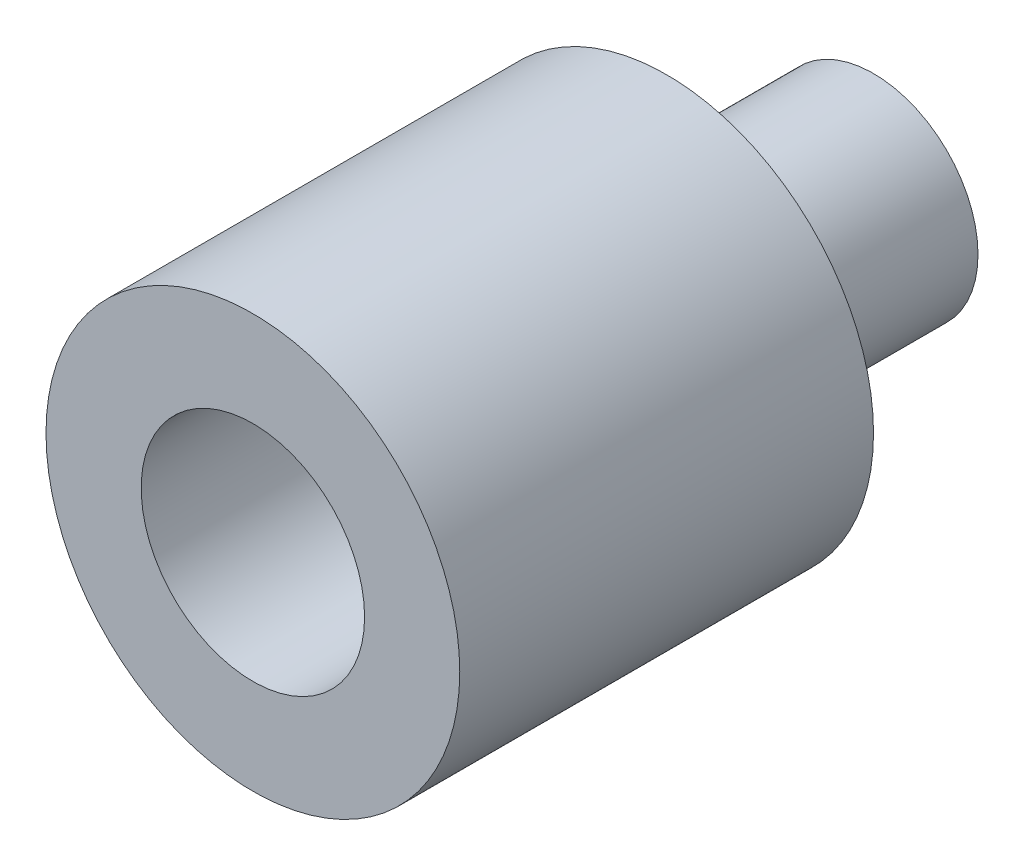
SolidWorks part; units mm, degrees
material "ABS"
ref_plane "X-Y Datum" through (0, 0, 0) normal (0, 0, 1) x (1, 0, 0)
ref_plane "X-Z Datum" through (0, 0, 0) normal (0, 1, 0) x (1, 0, 0)
ref_plane "Y-Z Datum" through (0, 0, 0) normal (1, 0, 0) x (0, 0, -1)
sketch "Sketch1" plane through (0, 0, 0) normal (0, 0, 1) x (1, 0, 0)
  circle A0 centre (0, 0) radius 2.525
  dimension "D1" = 5.05
extrude "Boss-Extrude1" add sketch "Sketch1" along normal blind 5
sketch "Sketch2" plane through (0, 0, 5) normal (0, 0, 1) x (1, 0, 0)
  circle A0 centre (0, 0) radius 5
  circle A1 centre (0, 0) radius 2.7 construction
  dimension "D1" = 5.4
  dimension "D2" = 10
extrude "Boss-Extrude2" add sketch "Sketch2" along normal blind 10 contours A0
sketch "Sketch3" plane through (0, 0, 15) normal (0, 0, 1) x (1, 0, 0)
  circle A0 centre (0, 0) radius 2.7
  dimension "D1" = 5.4
extrude "Cut-Extrude1" cut sketch "Sketch3" against normal blind 8
